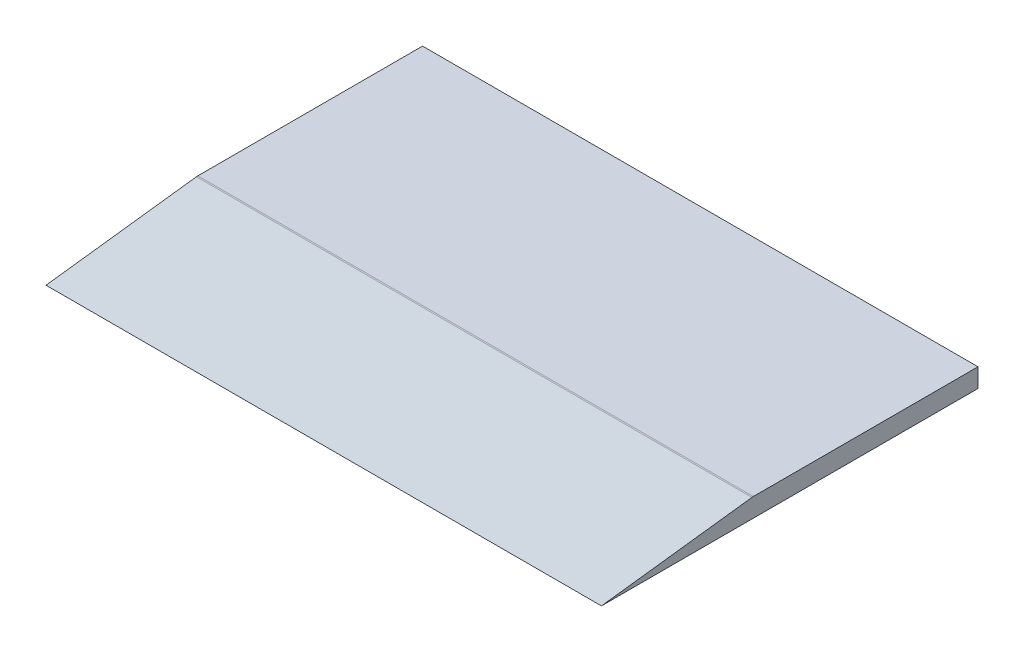
SolidWorks part; units mm, degrees
material "AISI 316 Stainless Steel Sheet (SS)"
ref_plane "Front Plane" through (0, 0, 0) normal (0, 0, 1) x (1, 0, 0)
ref_plane "Top Plane" through (0, 0, 0) normal (0, 1, 0) x (1, 0, 0)
ref_plane "Right Plane" through (0, 0, 0) normal (1, 0, 0) x (0, 0, -1)
sketch "Sketch2" plane through (0, 0, 0) normal (0, 1, 0) x (1, 0, 0)
  line L1 (0, 0) -> (374.6754, 0)
  line L2 (0, 0) -> (0, 254)
  line L3 (0, 254) -> (374.6754, 254)
  line L4 (374.6754, 0) -> (374.6754, 254)
  dimension "D1" = 254
  dimension "D2" = 374.6754
extrude "Boss-Extrude2" add sketch "Sketch2" along normal blind 12.7
sketch "Sketch4" plane through (374.6754, 0, 0) normal (1, 0, 0) x (0, 0, -1)
  line L0 (101.9617, 12.7) -> (0, 0)
  line L1 (0, 12.7) -> (254, 12.7) construction
  line L2 (0, 0) -> (254, 0) construction
  line L3 (0, 0) -> (0, 12.7)
  line L4 (0, 12.7) -> (101.9617, 12.7)
  dimension "D1" = 7.1
extrude "Cut-Extrude1" cut sketch "Sketch4" against normal through all contours L4 L0 L3
fillet "Fillet1" radius 7.62 1 edges at (187.3377, 12.7, -101.9617)
